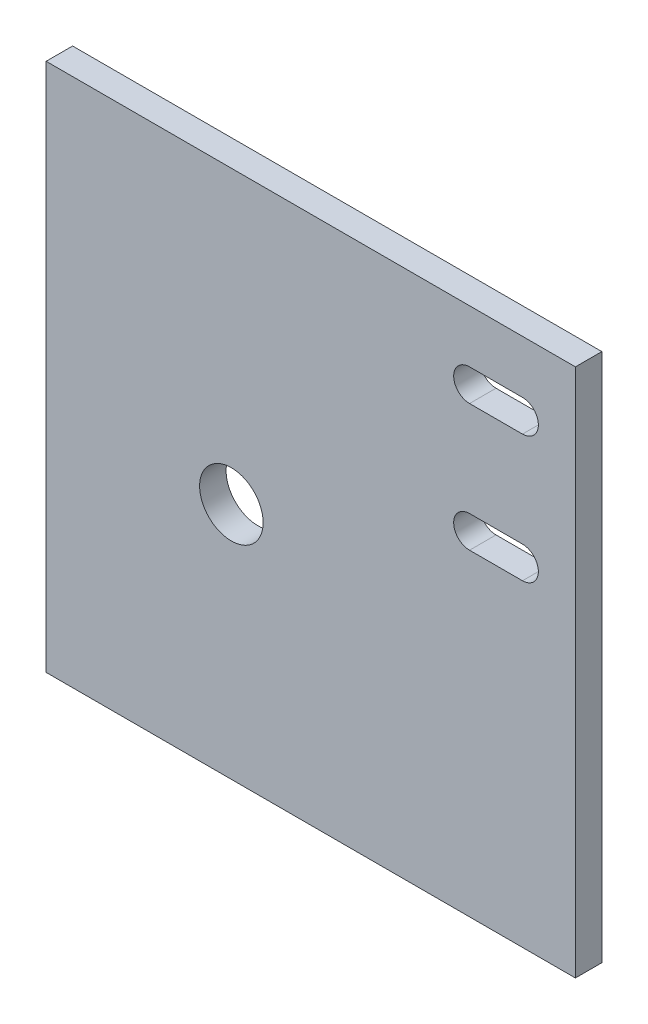
SolidWorks part; units mm, degrees
ref_plane "Plan de face" through (0, 0, 0) normal (0, 0, 1) x (1, 0, 0)
ref_plane "Plan de dessus" through (0, 0, 0) normal (0, 1, 0) x (1, 0, 0)
ref_plane "Plan de droite" through (0, 0, 0) normal (1, 0, 0) x (0, 0, -1)
sketch "Esquisse1" plane through (0, 0, 0) normal (0, 0, 1) x (1, 0, 0)
  line L1 (0, 0) -> (100, 0)
  line L2 (0, 0) -> (0, -100)
  line L3 (0, -100) -> (100, -100)
  line L4 (100, 0) -> (100, -100)
  line L5 (80, -10) -> (90, -10)
  line L7 (80, -16) -> (90, -16)
  line L9 (80, -34) -> (90, -34)
  line L11 (80, -40) -> (90, -40)
  arc A0 (90, -16) -> (90, -10) centre (90, -13) ccw
  arc A1 (80, -10) -> (80, -16) centre (80, -13) ccw
  arc A2 (80, -34) -> (80, -40) centre (80, -37) ccw
  arc A3 (90, -40) -> (90, -34) centre (90, -37) ccw
  point P14 (87.0149, -59.2985)
  point P16 (90, -59)
  dimension "D6" = 6
  dimension "D5" = 3
  dimension "D9" = 3
  dimension "D10" = 3
  dimension "D11" = 3
  dimension "D2" = 100
  dimension "D3" = 10
  dimension "D4" = 10
  dimension "D7" = 60
  dimension "D8" = 10
  dimension "D12" = 18
  dimension "D13" = 10
  dimension "D14" = 20
  dimension "D15" = 6
extrude "Boss.-Extru.1" add sketch "Esquisse1" along normal blind 5
sketch "Esquisse2" plane through (0, 0, 5) normal (0, 0, 1) x (1, 0, 0)
  line L1 (0, 0) -> (0, -100) construction
  line L3 (100, 0) -> (0, 0) construction
  circle A0 centre (35, -55) radius 6
  dimension "D1" = 12
  dimension "D2" = 55
  dimension "D3" = 35
extrude "Enlèv. mat.-Extru.1" cut sketch "Esquisse2" against normal blind 5
